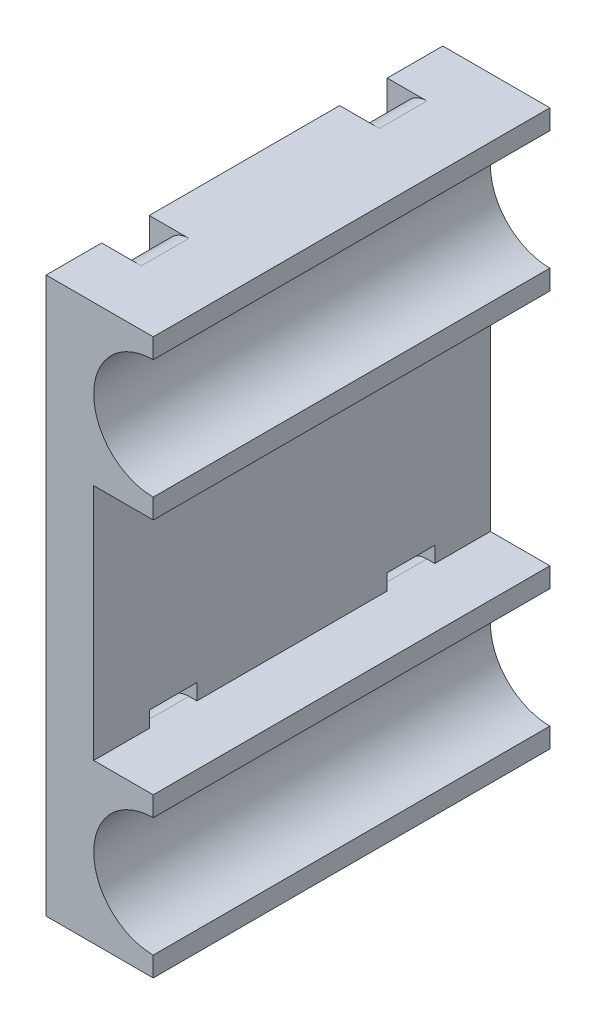
SolidWorks part; units mm, degrees
ref_plane "Plano frontal" through (0, 0, 0) normal (0, 0, 1) x (1, 0, 0)
ref_plane "Plano superior" through (0, 0, 0) normal (0, 1, 0) x (1, 0, 0)
ref_plane "Plano direito" through (0, 0, 0) normal (1, 0, 0) x (0, 0, -1)
sketch "Esboço1" plane through (0, 0, 0) normal (0, 0, 1) x (1, 0, 0)
  line L0 (0, 0) -> (67.7245, 0) construction
  line L1 (0, 35) -> (0, -35)
  line L2 (0, -35) -> (13.5, -35)
  line L3 (13.5, -35) -> (13.5, -32.5)
  line L4 (13.5, -17.5) -> (13.5, -15)
  line L5 (13.5, -15) -> (6, -15)
  line L6 (6, -15) -> (6, 15)
  line L7 (6, 15) -> (13.5, 15)
  line L8 (13.5, 15) -> (13.5, 17.5)
  line L9 (13.5, 32.5) -> (13.5, 35)
  line L10 (13.5, 35) -> (0, 35)
  arc A0 (13.5, 32.5) -> (13.5, 17.5) centre (13.5, 25) ccw
  arc A1 (13.5, -17.5) -> (13.5, -32.5) centre (13.5, -25) ccw
  point P3 (0, 0)
  dimension "D1" = 15
  dimension "D2" = 50
  dimension "D3" = 6
  dimension "D4" = 70
extrude "Ressalto-extrusão1" add sketch "Esboço1" along normal blind 50
sketch "Esboço2" plane through (6, 0, 0) normal (1, 0, 0) x (0, 0, -1)
  line L1 (-25, 15) -> (-25, -15) construction
  line L2 (-50, -15) -> (0, -15) construction
  line L3 (0, 0) -> (-50, 0) construction
  line L4 (-50, -15) -> (-50, 15) construction
  line L5 (-43, 15) -> (-37, 13) construction
  line L6 (-43, 13) -> (-37, 15) construction
  line L7 (-50, 15) -> (0, 15) construction
  line L8 (-7, 13) -> (-13, 13)
  line L9 (-7, 13) -> (-7, 15)
  line L10 (-7, 15) -> (-13, 15)
  line L11 (-13, 13) -> (-13, 15)
  line L12 (-7, 13) -> (-13, 15) construction
  line L13 (-7, 15) -> (-13, 13) construction
  line L15 (-37, 13) -> (-37, 15)
  line L16 (-43, 15) -> (-37, 15)
  line L17 (-43, 13) -> (-43, 15)
  line L18 (-43, 13) -> (-37, 13)
  line L19 (-7, -15) -> (-13, -13) construction
  line L20 (-7, -13) -> (-13, -15) construction
  line L21 (-43, -13) -> (-37, -15) construction
  line L22 (-43, -15) -> (-37, -13) construction
  line L23 (-43, -13) -> (-37, -13)
  line L24 (-43, -13) -> (-43, -15)
  line L25 (-43, -15) -> (-37, -15)
  line L26 (-37, -13) -> (-37, -15)
  line L27 (-13, -13) -> (-13, -15)
  line L28 (-7, -15) -> (-13, -15)
  line L29 (-7, -13) -> (-7, -15)
  line L30 (-7, -13) -> (-13, -13)
  line L31 (0, -15) -> (0, 15) construction
  point P7 (-10, 14)
  point P19 (-40, 14)
  point P29 (-40, -14)
  point P30 (-10, -14)
  dimension "D1" = 6
  dimension "D2" = 2
  dimension "D3" = 10
extrude "Corte-extrusão1" cut sketch "Esboço2" against normal blind 10
sketch "Esboço3" plane through (0, 0, 0) normal (-1, 0, 0) x (0, 0, 1)
  line L0 (50, 35) -> (0, 35) construction
  line L1 (13, 15) -> (7, 15)
  line L2 (13, 15) -> (13, 35)
  line L3 (13, 35) -> (7, 35)
  line L4 (7, 15) -> (7, 35)
  line L5 (25, 35) -> (25, -35) construction
  line L6 (50, -35) -> (0, -35) construction
  line L7 (0, 0) -> (50, 0) construction
  line L8 (50, 35) -> (50, -35) construction
  line L9 (43, 15) -> (43, 35)
  line L10 (37, 35) -> (43, 35)
  line L11 (37, 15) -> (37, 35)
  line L12 (37, 15) -> (43, 15)
  line L13 (37, -15) -> (43, -15)
  line L14 (37, -15) -> (37, -35)
  line L15 (37, -35) -> (43, -35)
  line L16 (43, -15) -> (43, -35)
  line L17 (7, -15) -> (7, -35)
  line L18 (13, -35) -> (7, -35)
  line L19 (13, -15) -> (13, -35)
  line L20 (13, -15) -> (7, -15)
extrude "Corte-extrusão2" cut sketch "Esboço3" against normal blind 2
fillet "Filete1" radius 3 8 edges at (2, -35, 10) (2, -35, 40) (2, 35, 40) (2, 35, 10) (2, -15, 10) (2, -15, 40) (2, 15, 40) (2, 15, 10)
sketch "Esboço4" plane through (6, 0, 0) normal (1, 0, 0) x (0, 0, -1)
  line L0 (0, -15) -> (0, 15) construction
  line L1 (0, -3.75) -> (-6.6629, -3.75)
  line L2 (0, -3.75) -> (0, -9.75)
  line L3 (0, -9.75) -> (-6.6629, -9.75)
  line L4 (-6.6629, -3.75) -> (-6.6629, -9.75)
  line L5 (0, 0) -> (-50, 0) construction
  line L6 (0, 3.75) -> (-6.6629, 3.75)
  line L7 (0, 3.75) -> (0, 9.75)
  line L8 (0, 9.75) -> (-6.6629, 9.75)
  line L9 (-6.6629, 3.75) -> (-6.6629, 9.75)
  line L10 (-50, -15) -> (-50, 15) construction
  dimension "D1" = 13.5
  dimension "D2" = 6
